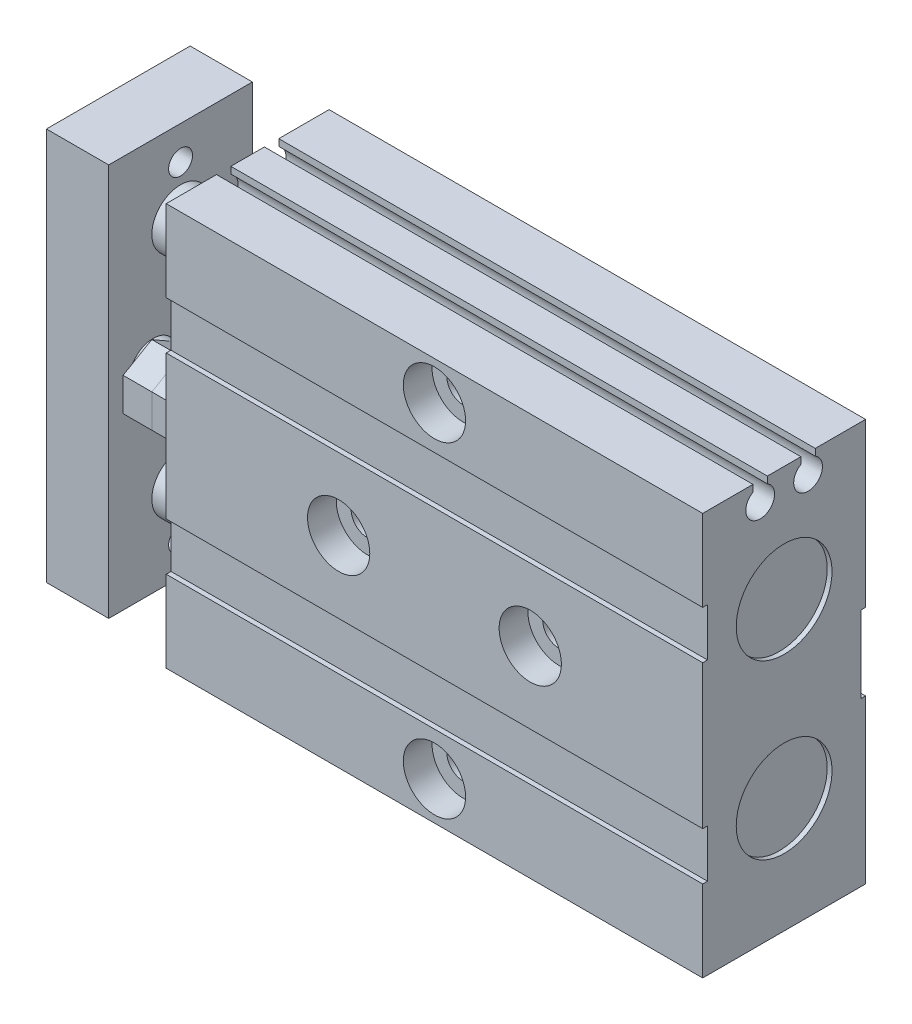
SolidWorks part; units mm, degrees
ref_plane "前视基准面" through (0, 0, 0) normal (0, 0, 1) x (1, 0, 0)
ref_plane "上视基准面" through (0, 0, 0) normal (0, 1, 0) x (1, 0, 0)
ref_plane "右视基准面" through (0, 0, 0) normal (1, 0, 0) x (0, 0, -1)
sketch "草图1" plane through (0, 0, 0) normal (0, 0, 1) x (1, 0, 0)
  line L1 (0, 0) -> (56, 0)
  line L2 (0, 0) -> (0, 42)
  line L3 (0, 42) -> (56, 42)
  line L4 (56, 0) -> (56, 42)
  dimension "D1" = 56
  dimension "D2" = 42
extrude "凸台-拉伸1" add sketch "草图1" along normal blind 17
sketch "草图2" plane through (0, 0, 0) normal (-1, 0, 0) x (0, 0, 1)
  line L0 (8.5, 42) -> (8.5, 0) construction
  line L1 (15.5, 19.2679) -> (15.5, 22.7321)
  line L2 (15.5, 22.7321) -> (12.5, 24.4641)
  line L3 (12.5, 24.4641) -> (9.5, 22.7321)
  line L4 (9.5, 22.7321) -> (9.5, 19.2679)
  line L5 (9.5, 19.2679) -> (12.5, 17.5359)
  line L6 (12.5, 17.5359) -> (15.5, 19.2679)
  line L7 (17, 42) -> (0, 42) construction
  line L8 (17, 0) -> (0, 0) construction
  line L9 (17, 21) -> (1.1064, 21) construction
  line L10 (17, 42) -> (17, 0) construction
  circle A0 centre (12.5, 21) radius 3 construction
  dimension "D1" = 4
  dimension "D2" = 3
extrude "凸台-拉伸2" add sketch "草图2" along normal blind 3 separate body
sketch "草图4" plane through (-3, 0, 0) normal (-1, 0, 0) x (0, 0, 1)
  line L0 (11, 23.5981) -> (14, 18.4019) construction
  line L1 (12.5, 24.4641) -> (9.5, 22.7321) construction
  line L2 (12.5, 17.5359) -> (15.5, 19.2679) construction
  line L3 (9.5, 19.2679) -> (12.5, 17.5359) construction
  line L4 (15.5, 19.2679) -> (15.5, 22.7321)
  line L5 (15.5, 22.7321) -> (12.5, 24.4641)
  line L6 (12.5, 24.4641) -> (9.5, 22.7321)
  line L7 (9.5, 22.7321) -> (9.5, 19.2679)
  line L8 (9.5, 19.2679) -> (12.5, 17.5359)
  line L9 (12.5, 17.5359) -> (15.5, 19.2679)
  line L10 (15.5, 19.2679) -> (15.5, 22.7321) construction
  circle A0 centre (12.5, 21) radius 3 construction
extrude "凸台-拉伸3" add sketch "草图4" along normal blind 3 separate body
sketch "草图5" plane through (0, 0, 0) normal (-1, 0, 0) x (0, 0, 1)
  line L0 (0, 21) -> (17, 21) construction
  line L1 (0, 42) -> (0, 0) construction
  line L2 (17, 42) -> (17, 0) construction
  line L3 (8.5, 42) -> (8.5, 0) construction
  line L4 (17, 42) -> (0, 42) construction
  line L5 (17, 0) -> (0, 0) construction
  circle A0 centre (8.5, 32.9617) radius 5
  circle A1 centre (8.5, 9.0383) radius 5
  dimension "D1" = 10
extrude "切除-拉伸1" cut sketch "草图5" against normal blind 0.5
sketch "草图6" plane through (56, 0, 0) normal (1, 0, 0) x (0, 0, -1)
  line L0 (-17, 21) -> (0, 21) construction
  line L1 (-17, 0) -> (-17, 42) construction
  line L2 (0, 0) -> (0, 42) construction
  line L3 (-8.5, 42) -> (-8.5, 0) construction
  line L4 (-17, 42) -> (0, 42) construction
  line L5 (-17, 0) -> (0, 0) construction
  circle A0 centre (-8.5, 30) radius 5
  circle A1 centre (-8.5, 12) radius 5
  dimension "D1" = 10
  dimension "D2" = 18
extrude "切除-拉伸2" cut sketch "草图6" against normal blind 0.5
sketch "草图7" plane through (0.5, 0, 0) normal (-1, 0, 0) x (0, 0, 1)
  circle A0 centre (8.5, 32.9617) radius 3
  circle A1 centre (8.5, 9.0383) radius 3
  dimension "D1" = 6
extrude "凸台-拉伸4" add sketch "草图7" along normal blind 7.5
sketch "草图8" plane through (-7, 0, 0) normal (-1, 0, 0) x (0, 0, 1)
  line L0 (8.5, 0) -> (8.5, 42) construction
  line L1 (1, 41.5) -> (16, 41.5)
  line L2 (1, 41.5) -> (1, 0.5)
  line L3 (1, 0.5) -> (16, 0.5)
  line L4 (16, 41.5) -> (16, 0.5)
  line L5 (17, 0) -> (0, 0) construction
  line L6 (17, 42) -> (0, 42) construction
  line L7 (0, 21) -> (17, 21) construction
  line L8 (0, 42) -> (0, 0) construction
  line L9 (17, 42) -> (17, 0) construction
  dimension "D1" = 1
  dimension "D2" = 0.5
extrude "凸台-拉伸5" add sketch "草图8" along normal blind 6.5
sketch "草图9" plane through (-7, 0, 0) normal (1, 0, 0) x (0, 0, -1)
  line L0 (-16, 21) -> (-0.5595, 21) construction
  line L1 (-16, 0.5) -> (-16, 41.5) construction
  circle A0 centre (-11.3628, 21) radius 2.5
  dimension "D1" = 5
extrude "凸台-拉伸6" add sketch "草图9" along normal blind 1
hole_wizard "M3 螺纹孔1" positions "草图12" profile "草图11" tap size "M3" standard "ISO"
sketch "草图12" plane through (-13.5, 0, 0) normal (-1, 0, 0) x (0, 0, 1)
  line L0 (1, 21) -> (16, 21) construction
  line L1 (1, 41.5) -> (1, 0.5) construction
  line L2 (16, 0.5) -> (16, 41.5) construction
  line L3 (8.5, 41.5) -> (8.5, 0.5) construction
  line L4 (16, 41.5) -> (1, 41.5) construction
  line L5 (1, 0.5) -> (16, 0.5) construction
  point P0 (8.5, 38)
  point P1 (8.5, 4)
  dimension "D1" = 34
sketch "草图11" plane through (-13.5, 38, 8.5) normal (0, 1, 0) x (0, 0, 1)
  line L0 (0, 0) -> (0, 8.2511)
  line L1 (0, 8.2511) -> (1.25, 7.5)
  line L2 (1.25, 7.5) -> (1.25, 0)
  line L5 (1.25, 0) -> (0, 0)
  line L10 (0, 8.2511) -> (-1.25, 7.5) construction
  line L11 (0, -6.35) -> (0, 107.95) construction
  dimension "螺纹孔钻头直径" = 2.5
  dimension "螺纹孔钻头深度" = 7.5
  dimension "导头角度" = 118
cosmetic thread "孔螺蚊线1" parameters "D1"=6, "D2"=3
cosmetic thread "孔螺蚊线2" parameters "D1"=6, "D2"=3
sketch "草图13" plane through (56, 0, 0) normal (1, 0, 0) x (0, 0, -1)
  line L0 (-8.5, 42) -> (-8.5, 37.5575) construction
  line L1 (-17, 42) -> (0, 42) construction
  circle A0 centre (-11, 40) radius 1.5
  circle A1 centre (-6, 40) radius 1.5
  dimension "D1" = 3
  dimension "D2" = 5
  dimension "D3" = 2
extrude "切除-拉伸3" cut sketch "草图13" against normal up to surface (56 mm away) up to face at (0, 9.0383, 3.5)
sketch "草图14" plane through (56, 0, 0) normal (1, 0, 0) x (0, 0, -1)
  line L0 (-17, 42) -> (0, 42) construction
  line L1 (-11.75, 42) -> (-10.25, 42)
  line L2 (-11.75, 42) -> (-11.75, 40)
  line L3 (-11.75, 40) -> (-10.25, 40)
  line L4 (-10.25, 42) -> (-10.25, 40)
  line L5 (-8.5, 42) -> (-8.5, 38.5062) construction
  line L6 (-11, 40) -> (-11, 42.9315) construction
  line L7 (-6.75, 42) -> (-6.75, 40)
  line L8 (-5.25, 40) -> (-6.75, 40)
  line L9 (-5.25, 42) -> (-5.25, 40)
  line L10 (-5.25, 42) -> (-6.75, 42)
  dimension "D1" = 2
  dimension "D2" = 1.5
extrude "切除-拉伸4" cut sketch "草图14" against normal up to surface (56 mm away) up to face at (0, 40, 4.5)
hole_wizard "M5 螺纹孔1" positions "草图16" profile "草图15" tap size "M5" standard "ISO"
sketch "草图16" plane through (0, 0, 0) normal (0, -1, 0) x (1, 0, 0)
  line L0 (56, 8.5) -> (0, 8.5) construction
  line L1 (56, 17) -> (56, 0) construction
  line L2 (0, 17) -> (0, 0) construction
  line L3 (0, 12.5) -> (0, 15.5) construction
  point P0 (11, 9.5)
  point P1 (45, 9.5)
  dimension "D1" = 1
  dimension "D2" = 11
  dimension "D3" = 11
sketch "草图15" plane through (11, 0, 9.5) normal (1, 0, 0) x (0, 0, -1)
  line L0 (0, 0) -> (0, 13.6618)
  line L1 (0, 13.6618) -> (2.1, 12.4)
  line L2 (2.1, 12.4) -> (2.1, 0)
  line L5 (2.1, 0) -> (0, 0)
  line L10 (0, 13.6618) -> (-2.1, 12.4) construction
  line L11 (0, -6.35) -> (0, 107.95) construction
  dimension "螺纹孔钻头直径" = 4.2
  dimension "螺纹孔钻头深度" = 12.4
  dimension "导头角度" = 118
cosmetic thread "孔螺蚊线3" parameters "D1"=10, "D2"=5
cosmetic thread "孔螺蚊线4" parameters "D1"=10, "D2"=5
sketch "草图17" plane through (0, 0, 0) normal (-1, 0, 0) x (0, 0, 1)
  line L0 (0, 42) -> (0, 0) construction
  line L1 (0, 25) -> (0.5, 25)
  line L2 (0, 25) -> (0, 17)
  line L3 (0, 17) -> (0.5, 17)
  line L4 (0.5, 25) -> (0.5, 17)
  line L5 (17, 42) -> (17, 0) construction
  line L6 (17, 33.5) -> (16.5, 33.5)
  line L7 (17, 33.5) -> (17, 28.5)
  line L8 (17, 28.5) -> (16.5, 28.5)
  line L9 (16.5, 33.5) -> (16.5, 28.5)
  line L10 (17, 21) -> (0, 21) construction
  line L11 (16.5, 8.5) -> (16.5, 13.5)
  line L12 (17, 13.5) -> (16.5, 13.5)
  line L13 (17, 8.5) -> (17, 13.5)
  line L14 (17, 8.5) -> (16.5, 8.5)
  line L15 (16.5, 11) -> (17, 11) construction
  line L16 (16.5, 31) -> (17, 31) construction
  dimension "D1" = 0.5
  dimension "D2" = 8
  dimension "D3" = 20
  dimension "D4" = 5
  dimension "D5" = 0.5
extrude "切除-拉伸5" cut sketch "草图17" against normal up to surface (56 mm away) up to face at (56, 34.2998, 8.5)
hole_wizard "M4 螺纹孔1" [suppressed] positions "草图19" profile "草图18" tap size "M4" standard "ISO"
sketch "草图19" plane through (0, 0, 17) normal (0, 0, 1) x (1, 0, 0)
  line L0 (28, 42) -> (28, 0) construction
  line L1 (56, 42) -> (0, 42) construction
  line L2 (0, 0) -> (56, 0) construction
  line L3 (56, 21) -> (0, 21) construction
  line L4 (56, 13.5) -> (56, 28.5) construction
  line L5 (0, 28.5) -> (0, 13.5) construction
  point P0 (18, 21)
  point P1 (38, 21)
  dimension "D1" = 20
sketch "草图18" plane through (18, 21, 17) normal (1, 0, 0) x (0, -1, 0)
  line L0 (0, 0) -> (0, 11.0914)
  line L1 (0, 11.0914) -> (1.65, 10.1)
  line L2 (1.65, 10.1) -> (1.65, 0)
  line L5 (1.65, 0) -> (0, 0)
  line L10 (0, 11.0914) -> (-1.65, 10.1) construction
  line L11 (0, -6.35) -> (0, 107.95) construction
  dimension "螺纹孔钻头直径" = 3.3
  dimension "螺纹孔钻头深度" = 10.1
  dimension "导头角度" = 118
cosmetic thread "孔螺蚊线5" [suppressed] parameters "D1"=8, "D2"=4
cosmetic thread "孔螺蚊线6" [suppressed] parameters "D1"=8, "D2"=4
hole_wizard "M3 六角凹头螺钉的柱形沉头孔1" positions "草图21" profile "草图20" counterbore size "M3" standard "ISO" end condition through all
sketch "草图21" plane through (0, 0, 17) normal (0, 0, 1) x (1, 0, 0)
  line L0 (0, 21) -> (56, 21) construction
  line L1 (0, 28.5) -> (0, 13.5) construction
  line L2 (56, 13.5) -> (56, 28.5) construction
  line L3 (28, 0) -> (28, 42) construction
  line L4 (0, 0) -> (56, 0) construction
  line L5 (56, 42) -> (0, 42) construction
  point P0 (18, 21)
  point P2 (28, 38)
  point P4 (28, 4)
  point P6 (38, 21)
  dimension "D1" = 18
  dimension "D2" = 34
  dimension "D3" = 20
sketch "草图20" plane through (18, 21, 17) normal (1, 0, 0) x (0, -1, 0)
  line L0 (0, 0) -> (0, 17)
  line L1 (0, 17) -> (1.7, 17)
  line L3 (1.7, 17) -> (1.7, 3)
  line L4 (1.7, 3) -> (3.25, 3)
  line L5 (3.25, 3) -> (3.25, 0)
  line L7 (3.25, 0) -> (0, 0)
  line L11 (0, -6.35) -> (0, 107.95) construction
  dimension "通孔孔直径" = 3.4
  dimension "通孔孔深度" = 17
  dimension "柱形沉头孔直径" = 6.5
  dimension "柱形沉头孔深度" = 3
sketch "草图22" plane through (0, 0, 0) normal (0, 0, -1) x (-1, 0, 0)
  circle A0 centre (-28, 38) radius 3.5
  circle A1 centre (-18, 21) radius 3.5
  circle A2 centre (-38, 21) radius 3.5
  circle A3 centre (-28, 4) radius 3.5
  dimension "D1" = 7
extrude "切除-拉伸10" cut sketch "草图22" against normal blind 4
